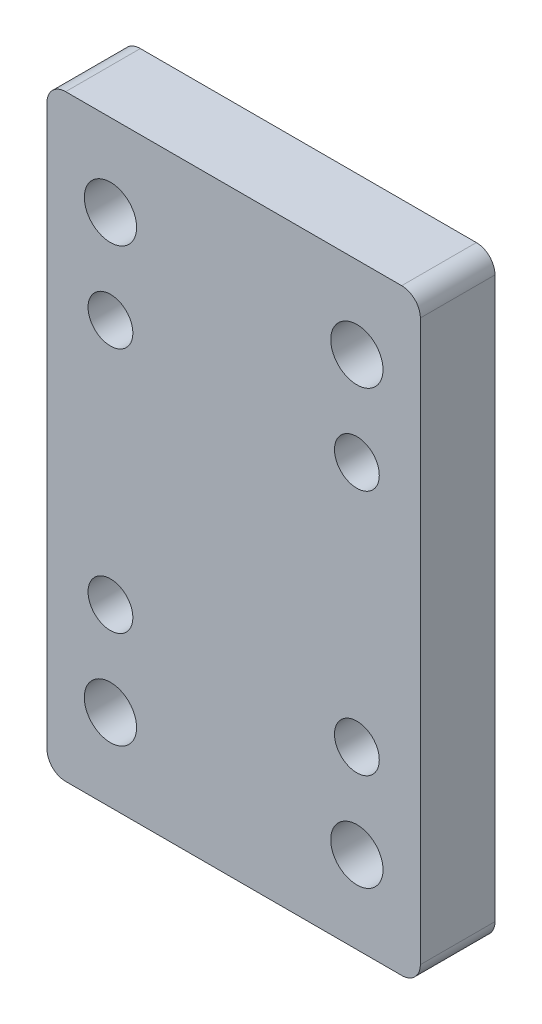
SolidWorks part; units mm, degrees
ref_plane "前视基准面" through (0, 0, 0) normal (0, 0, 1) x (1, 0, 0)
ref_plane "上视基准面" through (0, 0, 0) normal (0, 1, 0) x (1, 0, 0)
ref_plane "右视基准面" through (0, 0, 0) normal (1, 0, 0) x (0, 0, -1)
sketch "草图1" plane through (0, 0, 0) normal (0, 0, 1) x (1, 0, 0)
  line L0 (0, 0) -> (-25, 0) construction
  line L1 (-25, -40) -> (25, -40)
  line L2 (-25, -40) -> (-25, 40)
  line L3 (-25, 40) -> (25, 40)
  line L4 (25, -40) -> (25, 40)
  line L5 (-25, -40) -> (25, 40) construction
  line L6 (-25, 40) -> (25, -40) construction
  line L7 (0, 0) -> (0, 40) construction
  line L8 (0, 0) -> (0, -10) construction
  circle A0 centre (0, 0) radius 15.25
  circle A1 centre (-16.5, 16.5) radius 3
  circle A2 centre (-16.5, 29) radius 3.5
  point P0 (0, 0)
  dimension "BA" = 30.5
  dimension "D2" = 33
  dimension "缸体L" = 6
  dimension "BP" = 7
  dimension "BE" = 80
  dimension "BC" = 50
  dimension "T" = 33
  dimension "BF" = 58
  dimension "BD" = 33
  dimension "BB" = 10
sketch "草图2" plane through (0, 0, 0) normal (0, 0, 1) x (1, 0, 0)
  line L0 (-25, 40) -> (25, 40) construction
  line L1 (-25, -40) -> (-25, 40) construction
  line L2 (-25, -40) -> (25, -40) construction
  line L3 (25, -40) -> (25, 40) construction
  line L4 (-25, 40) -> (25, 40)
  line L5 (-25, -40) -> (-25, 40)
  line L6 (-25, -40) -> (25, -40)
  line L7 (25, -40) -> (25, 40)
extrude "凸台-拉伸1" add sketch "草图2" along normal blind 10
sketch "草图3" plane through (0, 0, 0) normal (0, 0, -1) x (-1, 0, 0)
  circle A0 centre (16.5, 29) radius 3.5 construction
  circle A1 centre (16.5, 16.5) radius 3 construction
  circle A2 centre (16.5, 29) radius 3.5
  circle A3 centre (16.5, 16.5) radius 3
extrude "切除-拉伸1" cut sketch "草图3" against normal through all
mirror "镜向1" about plane through (0, 0, 0) normal (1, 0, 0) of "切除-拉伸1"
mirror "镜向2" about plane through (0, 0, 0) normal (0, 1, 0) of "镜向1", "切除-拉伸1"
fillet "圆角1" radius 2.5 4 edges at (25, -40, 5) (-25, -40, 5) (-25, 40, 5) (25, 40, 5)
equation "\"D2@草图1\" = \"T@草图1\""
equation "\"D1@凸台-拉伸1\" = \"BB@草图1\""
equation "\"D1@圆角1\" = \"BC@草图1\"*0.05"
